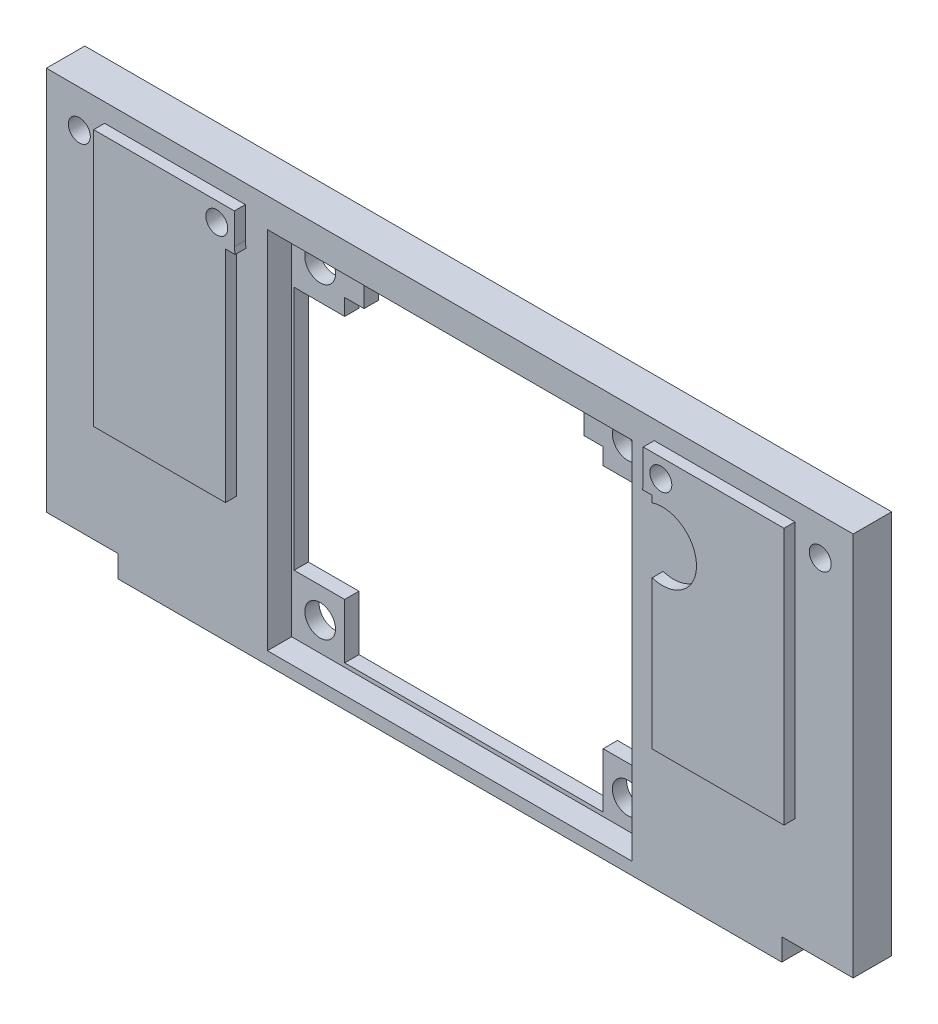
SolidWorks part; units mm, degrees
ref_plane "Front Plane" through (0, 0, 0) normal (0, 0, 1) x (1, 0, 0)
ref_plane "Top Plane" through (0, 0, 0) normal (0, 1, 0) x (1, 0, 0)
ref_plane "Right Plane" through (0, 0, 0) normal (1, 0, 0) x (0, 0, -1)
sketch "Sketch3" plane through (0, 0, 0) normal (0, 0, 1) x (1, 0, 0)
  line L0 (-39.9368, -0.9626) -> (-39.9368, 36.0374)
  line L1 (-3.2168, 30.7779) -> (-3.2168, 32.6429) construction
  line L2 (-34.7809, 21.6224) -> (-21.3928, 21.6224) construction
  line L3 (-30.5893, -0.9626) -> (18.3407, -0.9626) construction
  line L4 (-9.7818, 10.2129) -> (-9.7818, 23.3429) construction
  line L5 (-9.7818, 23.3429) -> (3.3482, 23.3429) construction
  line L6 (3.3482, 23.3429) -> (3.3482, 10.2129) construction
  line L7 (3.3482, 10.2129) -> (-9.7818, 10.2129) construction
  line L9 (-39.9368, -0.9626) -> (-14.8318, -0.9626)
  line L10 (-14.9818, 0.5374) -> (-14.9818, 5.5374)
  line L11 (-14.9818, 29.3429) -> (8.5482, 29.3429)
  line L12 (8.5482, 29.3429) -> (8.5482, 27.8429)
  line L13 (7.2982, -0.9626) -> (33.5032, -0.9626)
  line L14 (33.5032, -0.9626) -> (33.5032, 36.0374)
  line L15 (33.5032, 36.0374) -> (-39.9368, 36.0374)
  line L16 (-36.9368, 32.6429) -> (-23.4268, 32.6429) construction
  line L17 (-23.4268, 32.6429) -> (16.9932, 32.6429) construction
  line L18 (16.9932, 32.6429) -> (30.5032, 32.6429) construction
  line L19 (-17.2168, 30.7779) -> (10.7832, 30.7779) construction
  line L20 (-3.2168, 30.7779) -> (-3.2168, 23.3429) construction
  line L21 (-3.2168, 23.3429) -> (-3.2168, 10.2129) construction
  line L22 (-3.2168, 32.6429) -> (-3.2168, 42.2345) construction
  line L23 (-14.8318, -0.9626) -> (7.2982, -0.9626)
  line L24 (8.5482, 0.5374) -> (-14.9818, 0.5374)
  line L25 (-14.9818, 27.8429) -> (-19.5818, 27.8429)
  line L26 (-19.5818, 27.8429) -> (-19.5818, 5.5374)
  line L27 (-19.5818, 5.5374) -> (-14.9818, 5.5374)
  line L28 (-14.9818, 27.8429) -> (-14.9818, 29.3429)
  line L29 (8.5482, 5.5374) -> (13.1482, 5.5374)
  line L30 (13.1482, 5.5374) -> (13.1482, 27.8429)
  line L31 (13.1482, 27.8429) -> (8.5482, 27.8429)
  line L32 (8.5482, 5.5374) -> (8.5482, 0.5374)
  line L35 (-17.2168, 30.7779) -> (-17.2168, 2.7779) construction
  line L36 (-17.2168, 2.7779) -> (10.7832, 2.7779) construction
  line L37 (10.7832, 2.7779) -> (10.7832, 30.7779) construction
  circle A0 centre (-17.2168, 30.7779) radius 1.4
  circle A1 centre (-36.9368, 32.6429) radius 1
  circle A2 centre (-23.4268, 32.6429) radius 1
  circle A3 centre (16.9932, 32.6429) radius 1
  circle A4 centre (30.5032, 32.6429) radius 1
  circle A5 centre (-36.9368, 32.6429) radius 1
  circle A6 centre (-23.4268, 32.6429) radius 1
  circle A7 centre (-17.2168, 30.7779) radius 1.4
  circle A8 centre (-17.2168, 2.7779) radius 1.4
  circle A9 centre (10.7832, 30.7779) radius 1.4
  circle A10 centre (10.7832, 2.7779) radius 1.4
  point P47 (10.8482, 27.8429)
  dimension "D16" = 2
  dimension "D17" = 2.8
  dimension "D1" = 13.51
  dimension "D2" = 40.42
  dimension "D3" = 13.51
  dimension "D4" = 3.3945
  dimension "D5" = 28
  dimension "D6" = 1.865
  dimension "D7" = 13.13
  dimension "D8" = 13.13
  dimension "D9" = 7.435
  dimension "D10" = 3
  dimension "D11" = 3
  dimension "D12" = 5.2
  dimension "D13" = 5.2
  dimension "D14" = 6
  dimension "D15" = 37
  dimension "D18" = 1.5
  dimension "D19" = 5
  dimension "D20" = 9.8
  dimension "D22" = 1.5
  dimension "D23" = 9.8
  dimension "D24" = 28
extrude "Boss-Extrude1" add sketch "Sketch3" along normal blind 3.5 contours L14 L15 L0 L9 L10 L11 L12 L13 A9 A4 A3 A2 A1 A0
sketch "Sketch13" plane through (0, 0, 0) normal (0, 0, -1) x (-1, 0, 0)
  line L0 (-33.5032, 36.0374) -> (39.9368, 36.0374) construction
  line L1 (-33.5032, 36.0374) -> (-16.1332, 36.0374)
  line L2 (-33.5032, 36.0374) -> (-33.5032, -0.9626)
  line L3 (-33.5032, -0.9626) -> (-16.1332, -0.9626)
  line L4 (-16.1332, 36.0374) -> (-16.1332, -0.9626)
  line L5 (39.9368, -0.9626) -> (-33.5032, -0.9626) construction
  line L7 (22.5668, 36.0374) -> (39.9368, 36.0374)
  line L8 (22.5668, 36.0374) -> (22.5668, -0.9626)
  line L9 (22.5668, -0.9626) -> (39.9368, -0.9626)
  line L10 (39.9368, 36.0374) -> (39.9368, -0.9626)
  line L11 (3.2168, 36.0374) -> (3.2168, 44.4839) construction
  line L12 (3.2168, 36.0374) -> (-16.1332, 36.0374) construction
  line L13 (3.2168, 36.0374) -> (22.5668, 36.0374) construction
  line L14 (-33.5032, -0.9626) -> (-33.5032, 36.0374) construction
  dimension "D1" = 38.7
extrude "Boss-Extrude3" [suppressed] add sketch "Sketch13" along normal blind 1
sketch "Sketch9" plane through (0, 0, 3.5) normal (0, 0, -1) x (-1, 0, 0)
  line L1 (-10.7832, 30.7779) -> (-8.9447, 28.9394) construction
  line L2 (17.2168, 2.7779) -> (17.2168, 30.7779) construction
  line L3 (17.2168, 30.7779) -> (-10.7832, 2.7779) construction
  line L4 (3.2168, 16.7779) -> (17.2168, 2.7779) construction
  line L5 (3.2168, 16.7779) -> (-10.7832, 30.7779) construction
  line L7 (-13.3832, 0.1779) -> (19.8168, 0.1779)
  line L8 (-13.3832, 0.1779) -> (-13.3832, 33.3779)
  line L9 (-13.3832, 33.3779) -> (19.8168, 33.3779)
  line L10 (19.8168, 0.1779) -> (19.8168, 33.3779)
  line L11 (-13.3832, 0.1779) -> (19.8168, 33.3779) construction
  line L12 (-13.3832, 33.3779) -> (19.8168, 0.1779) construction
  dimension "D2" = 33.2
extrude "Cut-Extrude1" cut sketch "Sketch9" along normal blind 2.2
sketch "Sketch10" plane through (0, 0, 0) normal (0, 0, -1) x (-1, 0, 0)
  line L0 (14.9818, 29.3429) -> (-8.5482, 29.3429) construction
  line L1 (-6.7832, 31.8429) -> (13.2168, 31.8429)
  line L2 (-6.7832, 31.8429) -> (-6.7832, 29.3429)
  line L3 (-6.7832, 29.3429) -> (13.2168, 29.3429)
  line L4 (13.2168, 31.8429) -> (13.2168, 29.3429)
  point P4 (3.2168, 29.3429)
  dimension "D1" = 2.5
  dimension "D2" = 20
extrude "Cut-Extrude2" cut sketch "Sketch10" against normal blind 1.75
sketch "Sketch11" plane through (0, 0, 3.5) normal (0, 0, 1) x (1, 0, 0)
  line L0 (-36.9368, 32.6429) -> (-23.4268, 32.6429) construction
  line L1 (-34.6368, 30.9429) -> (-34.6368, 10.9429)
  line L9 (-21.8268, 34.3429) -> (-34.6368, 34.3429)
  line L14 (-34.6368, 30.9429) -> (-34.6368, 34.3429)
  line L17 (-34.6368, 10.9429) -> (-22.6368, 10.9429)
  line L18 (-22.6368, 30.9429) -> (-22.6368, 10.9429)
  line L19 (-27.6818, 10.9429) -> (-27.6818, 4.0347) construction
  line L20 (-21.8268, 34.3429) -> (-21.8268, 31.5137)
  line L21 (-22.6368, 30.9429) -> (-21.7519, 30.9429)
  circle A1 centre (-36.9368, 32.6429) radius 1 construction
  circle A2 centre (-23.4268, 32.6429) radius 1
  circle A5 centre (-23.4268, 32.6429) radius 1 construction
  arc A6 (-21.8268, 31.5137) -> (-21.7519, 30.9429) centre (-18.1406, 31.707) ccw
  point P2 (-27.6818, 32.6429)
  point P16 (-34.6368, 32.6429)
  dimension "D1" = 1.6
  dimension "D2" = 12
  dimension "D3" = 2.3
  dimension "D5" = 20
extrude "Boss-Extrude2" add sketch "Sketch11" along normal blind 1
ref_plane "Plane1" through (-3.2168, 0, 0) normal (-1, 0, 0) x (0, 0, 1)
mirror "Mirror1" about plane through (-3.2168, 0, 0) normal (-1, 0, 0) of "Boss-Extrude2"
sketch "Sketch14" plane through (0, 0, 4.5) normal (0, 0, 1) x (1, 0, 0)
  circle A1 centre (17.1422, 27.3923) radius 3.1
  circle A2 centre (16.9932, 32.6429) radius 1 construction
  circle A3 centre (30.5032, 32.6429) radius 1 construction
  dimension "D1" = 6.2
  dimension "D2" = 5.2506
  dimension "D3" = 13.361
extrude "Cut-Extrude3" cut sketch "Sketch14" against normal up to surface (1 mm away) up to face at (19.2755, 26.2814, 3.5)
sketch "Sketch15" plane through (0, 0, 3.5) normal (0, 0, 1) x (1, 0, 0)
  line L1 (-39.9368, -0.9626) -> (-33.4368, -0.9626)
  line L2 (-39.9368, -0.9626) -> (-39.9368, 1.0374)
  line L3 (-39.9368, 1.0374) -> (-33.4368, 1.0374)
  line L4 (-33.4368, -0.9626) -> (-33.4368, 1.0374)
  line L5 (33.5032, -0.9626) -> (27.0032, -0.9626)
  line L6 (33.5032, -0.9626) -> (33.5032, 1.0374)
  line L7 (33.5032, 1.0374) -> (27.0032, 1.0374)
  line L8 (27.0032, -0.9626) -> (27.0032, 1.0374)
  dimension "D1" = 6.5
  dimension "D2" = 2
extrude "Cut-Extrude4" cut sketch "Sketch15" against normal through all
